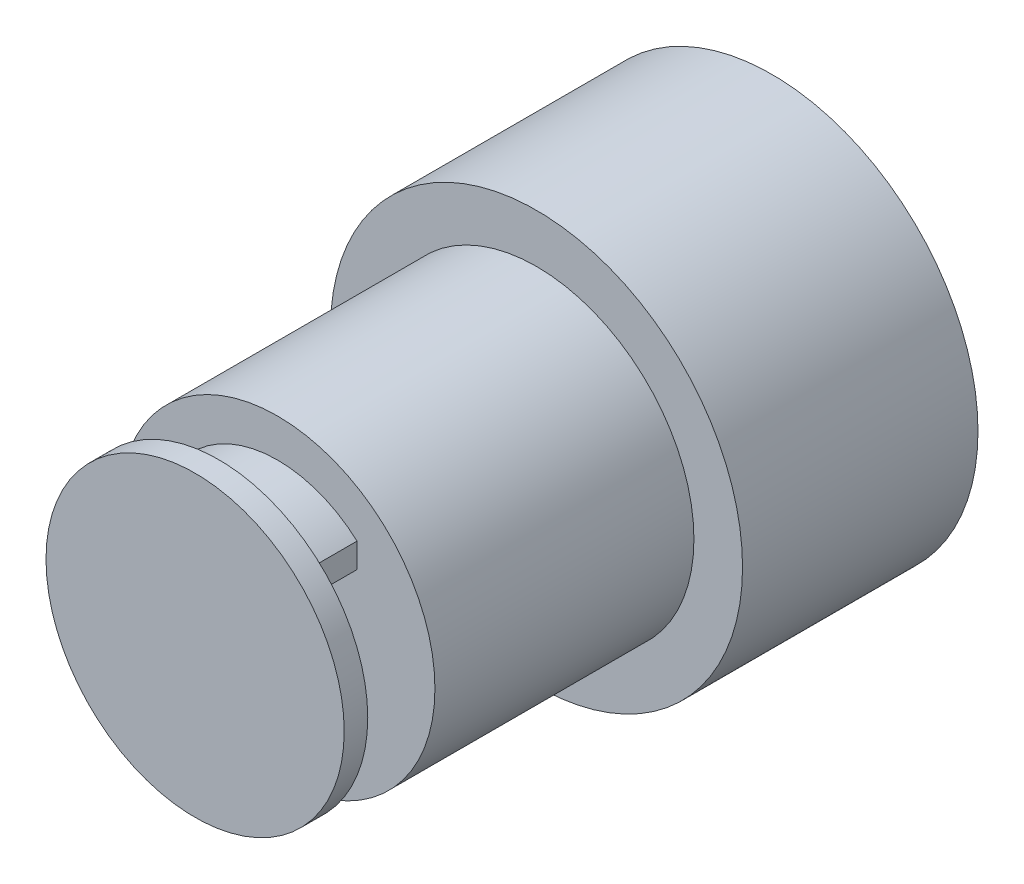
SolidWorks part; units mm, degrees
ref_plane "Front Plane" through (0, 0, 0) normal (0, 0, 1) x (1, 0, 0)
ref_plane "Top Plane" through (0, 0, 0) normal (0, 1, 0) x (1, 0, 0)
ref_plane "Right Plane" through (0, 0, 0) normal (1, 0, 0) x (0, 0, -1)
sketch "Sketch1" plane through (0, 0, 0) normal (0, 0, 1) x (1, 0, 0)
  circle A0 centre (0, 0) radius 17.5
  dimension "D1" = 35
extrude "Boss-Extrude1" add sketch "Sketch1" along normal blind 20
sketch "Sketch2" plane through (0, 0, 20) normal (0, 0, 1) x (1, 0, 0)
  circle A0 centre (0, 0) radius 13.3711
extrude "Boss-Extrude2" add sketch "Sketch2" along normal blind 22
sketch "Sketch3" plane through (0, 0, 42) normal (0, 0, 1) x (1, 0, 0)
  line L0 (-6.7594, 7.5476) -> (-6.7594, 5.4523)
  line L1 (6.7594, 7.5476) -> (6.7594, 5.4523)
  line L2 (-6.7594, -5.4523) -> (-6.7594, -7.5476)
  line L3 (6.7594, -5.4523) -> (6.7594, -7.5476)
  arc A0 (-6.7594, -7.5476) -> (6.7594, -7.5476) centre (0, 0) ccw
  arc A1 (-6.7594, -5.4523) -> (6.7594, -5.4523) centre (0, 0) ccw
  arc A2 (6.7594, 7.5476) -> (-6.7594, 7.5476) centre (0, 0) ccw
  arc A3 (6.7594, 5.4523) -> (-6.7594, 5.4523) centre (0, 0) ccw
extrude "Boss-Extrude3" add sketch "Sketch3" along normal blind 5
sketch "Sketch4" plane through (0, 0, 47) normal (0, 0, 1) x (1, 0, 0)
  circle A0 centre (0, 0) radius 12.665
extrude "Boss-Extrude4" add sketch "Sketch4" along normal blind 2
sketch "Sketch5" plane through (0, 0, 0) normal (0, 0, -1) x (-1, 0, 0)
  circle A0 centre (0, -10) radius 2.5
  dimension "D1" = 5
  dimension "D2" = 10
extrude "Boss-Extrude5" add sketch "Sketch5" along normal blind 20
sketch "Sketch6" plane through (0, 0, 0) normal (0, 0, -1) x (-1, 0, 0)
  circle A0 centre (0, -10) radius 6
  circle A2 centre (0, -10) radius 2.5
  circle A3 centre (0, -10) radius 2.5
  dimension "D1" = 12
  dimension "D2" = 0
extrude "Boss-Extrude6" add sketch "Sketch6" along normal blind 4
sketch "Sketch8" plane through (0, 0, -20) normal (0, 0, -1) x (-1, 0, 0)
  circle A1 centre (0, -10) radius 2.5
  circle A2 centre (0, -10) radius 2.5
  dimension "D1" = 0
extrude "Cut-Extrude1" cut sketch "Sketch8" against normal blind 25
